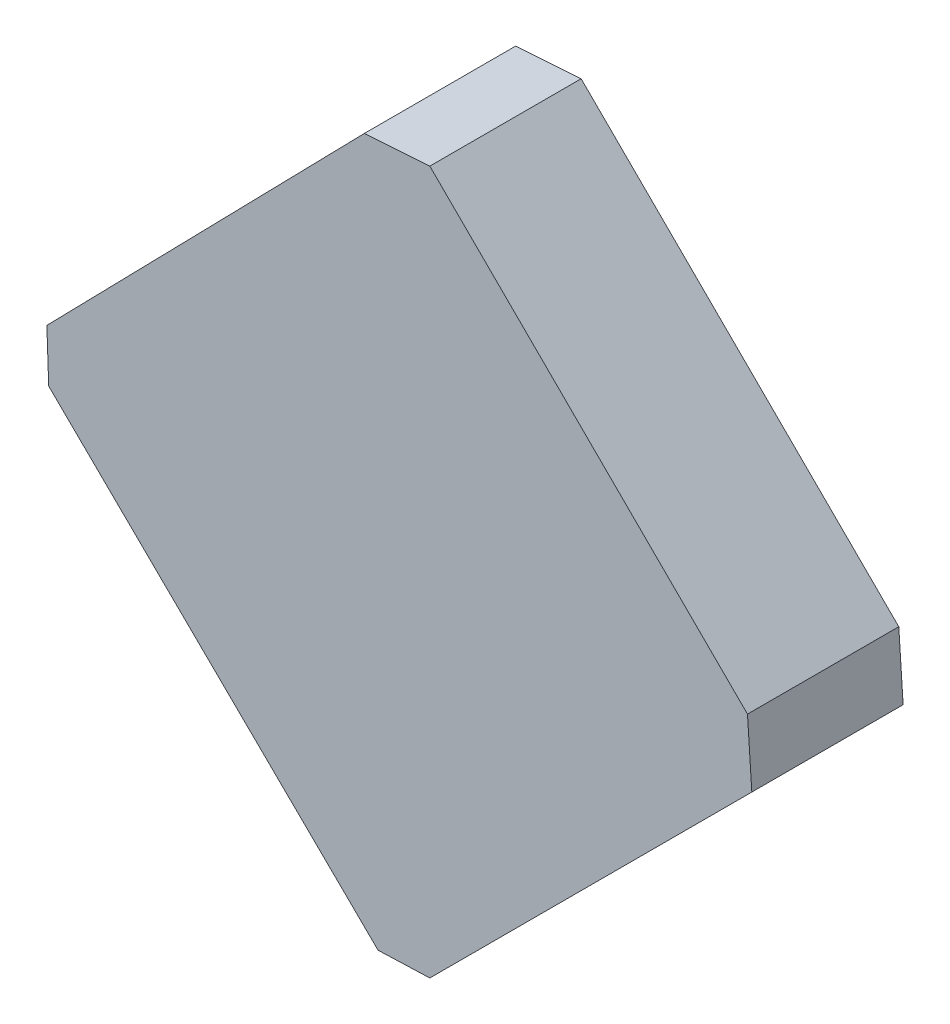
SolidWorks part; units mm, degrees
ref_plane "Front Plane" through (0, 0, 0) normal (0, 0, 1) x (1, 0, 0)
ref_plane "Top Plane" through (0, 0, 0) normal (0, 1, 0) x (1, 0, 0)
ref_plane "Right Plane" through (0, 0, 0) normal (1, 0, 0) x (0, 0, -1)
sketch "Sketch1" plane through (0, 0, 0) normal (0, 0, 1) x (1, 0, 0)
  line L0 (-11.6467, 0.763) -> (-1.1535, 11.5037)
  line L1 (-1.1535, 11.5037) -> (1.0072, 11.6467)
  line L2 (1.0072, 11.6467) -> (11.5037, 1.2141)
  line L3 (11.5037, 1.2141) -> (11.6467, -0.9465)
  line L4 (11.6467, -0.9465) -> (1.0072, -11.5861)
  line L5 (1.0072, -11.5861) -> (-0.7024, -11.6467)
  line L6 (-0.7024, -11.6467) -> (-11.5861, -0.9465)
  line L7 (-11.5861, -0.9465) -> (-11.6467, 0.763)
extrude "Boss-Extrude1" add sketch "Sketch1" along normal blind 5
